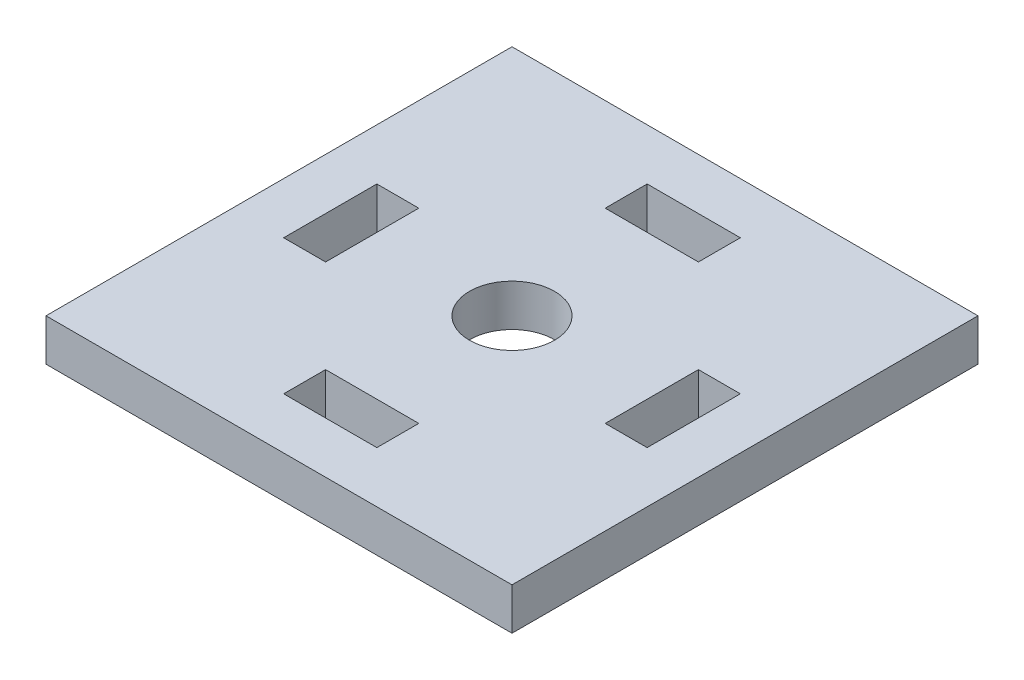
SolidWorks part; units mm, degrees
ref_plane "Front Plane" through (0, 0, 0) normal (0, 0, 1) x (1, 0, 0)
ref_plane "Top Plane" through (0, 0, 0) normal (0, 1, 0) x (1, 0, 0)
ref_plane "Right Plane" through (0, 0, 0) normal (1, 0, 0) x (0, 0, -1)
other "Configuration Table"
sketch "Sketch1" plane through (0, 0, 0) normal (0, 1, 0) x (1, 0, 0)
  line L23 (-22.8832, 0.4037) -> (-22.8832, -49.5963) construction
  line L40 (-47.8832, -24.5963) -> (2.1168, -24.5963) construction
  line L75 (-42.3832, -44.0963) -> (-42.3832, -5.0963) construction
  line L84 (-42.3832, -5.0963) -> (-3.3832, -5.0963) construction
  line L85 (-42.3832, -19.5963) -> (-37.8832, -19.5963)
  line L106 (-42.3832, -19.5963) -> (-42.3832, -29.5963)
  line L115 (-42.3832, -29.5963) -> (-37.8832, -29.5963)
  line L118 (-37.8832, -19.5963) -> (-37.8832, -29.5963)
  line L132 (-17.8832, -5.0963) -> (-27.8832, -5.0963)
  line L133 (-47.8832, 0.4037) -> (2.1168, 0.4037)
  line L134 (-47.8832, 0.4037) -> (-47.8832, -49.5963)
  line L135 (-47.8832, -49.5963) -> (2.1168, -49.5963)
  line L136 (2.1168, 0.4037) -> (2.1168, -49.5963)
  line L137 (-3.3832, -5.0963) -> (-3.3832, -44.0963) construction
  line L138 (-3.3832, -44.0963) -> (-42.3832, -44.0963) construction
  line L139 (-17.8832, -5.0963) -> (-17.8832, -9.5963)
  line L140 (-17.8832, -9.5963) -> (-27.8832, -9.5963)
  line L141 (-27.8832, -5.0963) -> (-27.8832, -9.5963)
  line L142 (-3.3832, -29.5963) -> (-3.3832, -19.5963)
  line L143 (-3.3832, -29.5963) -> (-7.8832, -29.5963)
  line L144 (-7.8832, -29.5963) -> (-7.8832, -19.5963)
  line L145 (-3.3832, -19.5963) -> (-7.8832, -19.5963)
  line L146 (-27.8832, -44.0963) -> (-17.8832, -44.0963)
  line L147 (-27.8832, -44.0963) -> (-27.8832, -39.5963)
  line L148 (-27.8832, -39.5963) -> (-17.8832, -39.5963)
  line L149 (-17.8832, -44.0963) -> (-17.8832, -39.5963)
  circle A0 centre (-22.8832, -24.5963) radius 4.5577
  point P30 (-22.8832, -24.5963)
  point P34 (-22.8832, -24.5963)
  point P38 (-22.8832, -24.5963)
  dimension "D3" = 4.5
  dimension "D4" = 10
  dimension "D6" = 4
  dimension "D7" = 50
  dimension "D8" = 50
  dimension "D9" = 5.5
  dimension "D10" = 5.5
extrude "Boss-Extrude1" add sketch "Sketch1" along normal blind 4.5
